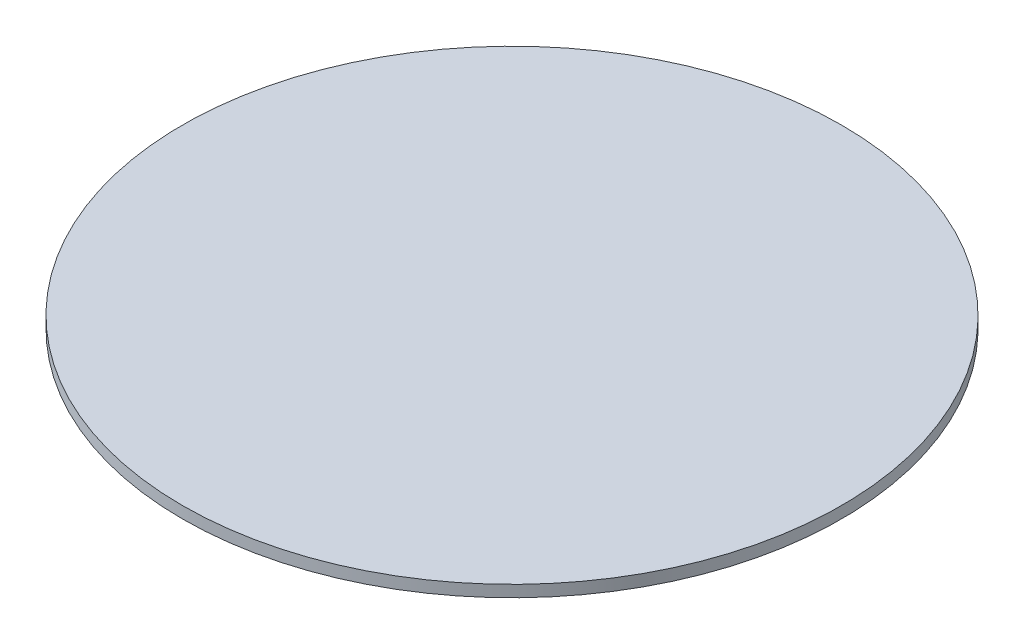
SolidWorks part; units mm, degrees
ref_plane "Front Plane" through (0, 0, 0) normal (0, 0, 1) x (1, 0, 0)
ref_plane "Top Plane" through (0, 0, 0) normal (0, 1, 0) x (1, 0, 0)
ref_plane "Right Plane" through (0, 0, 0) normal (1, 0, 0) x (0, 0, -1)
sketch "Sketch1" plane through (0, 0, 0) normal (0, 1, 0) x (1, 0, 0)
  circle A0 centre (0, 0) radius 42.5
  dimension "D1" = 85
extrude "Boss-Extrude1" add sketch "Sketch1" along normal blind 1.5
